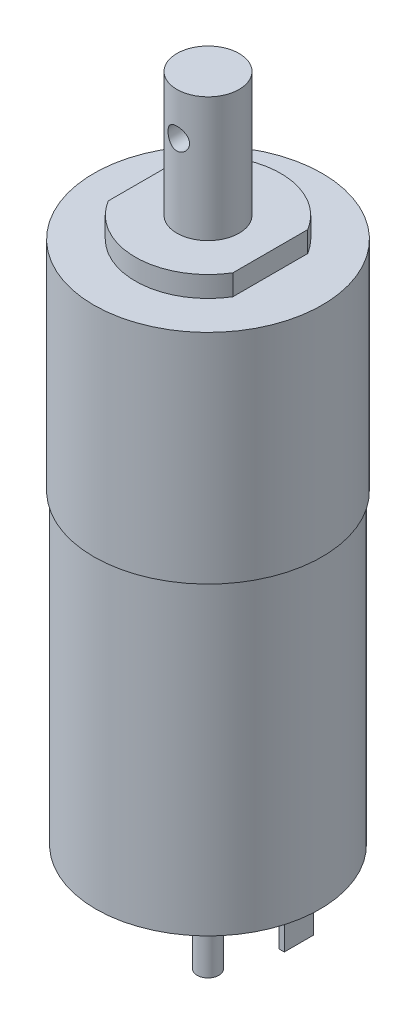
SolidWorks part; units mm, degrees
material "201 Annealed Stainless Steel (SS)"
ref_plane "Front Plane" through (0, 0, 0) normal (0, 0, 1) x (1, 0, 0)
ref_plane "Top Plane" through (0, 0, 0) normal (0, 1, 0) x (1, 0, 0)
ref_plane "Right Plane" through (0, 0, 0) normal (1, 0, 0) x (0, 0, -1)
sketch "Sketch2" plane through (0, 0, 0) normal (0, 1, 0) x (1, 0, 0)
  circle A0 centre (0, 0) radius 10.8
  dimension "D1" = 21.6
extrude "Boss-Extrude1" add sketch "Sketch2" along normal blind 29.5
sketch "Sketch3" plane through (0, 29.5, 0) normal (0, 1, 0) x (1, 0, 0)
  circle A0 centre (0, 0) radius 11
  dimension "D1" = 22
extrude "Boss-Extrude2" add sketch "Sketch3" along normal blind 21
sketch "Sketch4" plane through (0, 50.5, 0) normal (0, 1, 0) x (1, 0, 0)
  line L0 (-6, 0) -> (6, 0) construction
  line L1 (6, 3.6056) -> (6, -3.6056)
  line L2 (-6, 3.6056) -> (-6, -3.6056)
  arc A0 (-6, -3.6056) -> (6, -3.6056) centre (0, 0) ccw
  arc A1 (6, 3.6056) -> (-6, 3.6056) centre (0, 0) ccw
  dimension "D1" = 14
  dimension "D2" = 12
extrude "Boss-Extrude3" add sketch "Sketch4" along normal blind 2
sketch "Sketch5" plane through (0, 52.5, 0) normal (0, 1, 0) x (1, 0, 0)
  circle A0 centre (0, 0) radius 3
  dimension "D1" = 6
extrude "Boss-Extrude4" add sketch "Sketch5" along normal blind 12
sketch "Sketch6" plane through (0, 0, 0) normal (0, -1, 0) x (1, 0, 0)
  circle A0 centre (0, 0) radius 3.75
  dimension "D1" = 7.5
extrude "Boss-Extrude5" add sketch "Sketch6" along normal blind 2
sketch "Sketch7" plane through (0, 0, 0) normal (0, -1, 0) x (1, 0, 0)
  line L0 (-8.25, 0) -> (8.25, 0) construction
  line L1 (-8.75, 1.4) -> (-8.25, 1.4)
  line L2 (-8.75, 1.4) -> (-8.75, -1.4)
  line L3 (-8.75, -1.4) -> (-8.25, -1.4)
  line L4 (-8.25, 1.4) -> (-8.25, -1.4)
  line L5 (8.25, 1.4) -> (8.75, 1.4)
  line L6 (8.25, 1.4) -> (8.25, -1.4)
  line L7 (8.25, -1.4) -> (8.75, -1.4)
  line L8 (8.75, 1.4) -> (8.75, -1.4)
  point P8 (8.75, 0)
  point P12 (0, 0)
  dimension "D1" = 2.8
  dimension "D2" = 0.5
  dimension "D3" = 16.5
extrude "Boss-Extrude6" add sketch "Sketch7" along normal blind 3.9
sketch "Sketch8" plane through (0, -2, 0) normal (0, -1, 0) x (1, 0, 0)
  circle A0 centre (0, 0) radius 1.05
  dimension "D1" = 2.1
extrude "Boss-Extrude7" add sketch "Sketch8" along normal blind 8.4
sketch "草图1" plane through (0, 0, 0) normal (0, 0, 1) x (1, 0, 0)
  line L0 (3, 64.5) -> (-3, 64.5) construction
  line L1 (6, 50.5) -> (-6, 50.5) construction
  circle A0 centre (0, 60.4) radius 1.0375
  point P6 (10.3325, 59.6101)
  point P7 (0, 50.5)
  dimension "D2" = 2.075
  dimension "D1" = 4.1
extrude "切除-拉伸1" cut sketch "草图1" against normal mid plane 10
